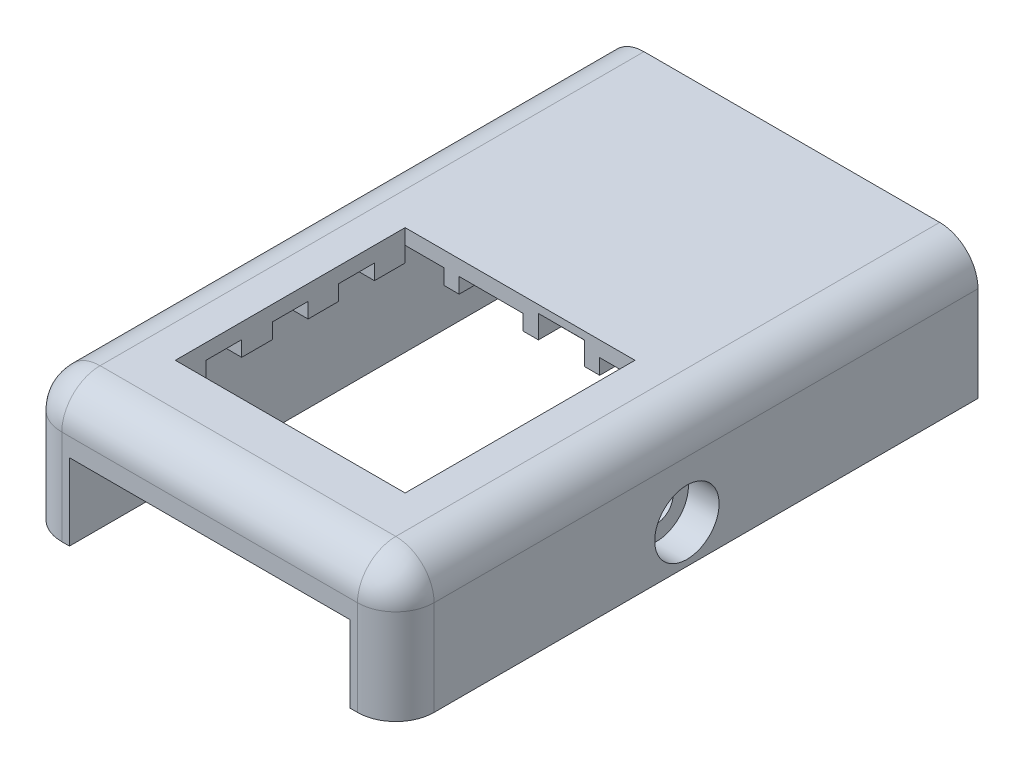
SolidWorks part; units mm, degrees
ref_plane "Front Plane" through (0, 0, 0) normal (0, 0, 1) x (1, 0, 0)
ref_plane "Top Plane" through (0, 0, 0) normal (0, 1, 0) x (1, 0, 0)
ref_plane "Right Plane" through (0, 0, 0) normal (1, 0, 0) x (0, 0, -1)
sketch "Sketch1" plane through (0, 0, 0) normal (0, 1, 0) x (1, 0, 0)
  line L1 (0, 0) -> (18, 0) construction
  line L2 (0, 0) -> (0, 31) construction
  line L3 (0, 31) -> (18, 31) construction
  line L4 (18, 0) -> (18, 31) construction
  line L5 (-3.15, 37.7) -> (21.15, 37.7)
  line L6 (-3.15, 37.7) -> (-3.15, -0.3)
  line L7 (-3.15, -0.3) -> (21.15, -0.3)
  line L8 (21.15, 37.7) -> (21.15, -0.3)
  line L9 (9, 0) -> (9, -0.3) construction
  dimension "D1" = 18
  dimension "D2" = 31
  dimension "D4" = 0.3
  dimension "D5" = 38
extrude "base" add sketch "Sketch1" along normal blind 2
sketch "Sketch2" plane through (0, 0, 0) normal (0, -1, 0) x (1, 0, 0)
  line L0 (9, 0) -> (9, 0.15) construction
  line L1 (-3.15, 0.3) -> (21.15, 0.3)
  line L2 (-3.15, 0.3) -> (-3.15, -37.7)
  line L3 (-3.15, -37.7) -> (21.15, -37.7)
  line L4 (21.15, 0.3) -> (21.15, -37.7)
  line L5 (-0.15, 0.15) -> (18.15, 0.15)
  line L6 (-0.15, 0.15) -> (-0.15, -31.15)
  line L7 (-0.15, -31.15) -> (18.15, -31.15)
  line L8 (18.15, 0.15) -> (18.15, -31.15)
  line L9 (18, -15.5) -> (18.15, -15.5) construction
  line L10 (-0.15, -15.5) -> (0, -15.5) construction
  line L11 (9, -31.15) -> (9, -31) construction
  line L13 (0, 0) -> (18, 0) construction
  line L14 (0, 0) -> (0, -31) construction
  line L15 (0, -31) -> (18, -31) construction
  line L16 (18, 0) -> (18, -31) construction
  dimension "D1" = 0.15
  dimension "D2" = 18
  dimension "D3" = 31
extrude "pcb_edge_walls" add sketch "Sketch2" along normal blind 1.7
sketch "Sketch3" plane through (0, 0, 0) normal (0, -1, 0) x (1, 0, 0)
  line L2 (0, 0) -> (18, 0) construction
  line L3 (0, 0) -> (0, -31) construction
  line L4 (0, -31) -> (18, -31) construction
  line L5 (18, 0) -> (18, -31) construction
  circle A0 centre (1.5, -29.46) radius 0.95
  circle A1 centre (16.5, -29.46) radius 0.95
  circle A2 centre (9, -3) radius 0.95
  point P9 (9, 0)
  dimension "D1" = 1.9
  dimension "D2" = 18
  dimension "D3" = 31
  dimension "D4" = 1.5
  dimension "D5" = 1.54
  dimension "D6" = 1.5
  dimension "D7" = 1.54
  dimension "D8" = 3
extrude "pcb_mount_dowels" add sketch "Sketch3" along normal blind 1.6
sketch "Sketch4" plane through (0, 2, 0) normal (0, 1, 0) x (1, 0, 0)
  line L0 (9, 19.96) -> (9, 12.46) construction
  line L1 (1.5, 4.96) -> (16.5, 4.96)
  line L2 (1.5, 4.96) -> (1.5, 19.96)
  line L3 (1.5, 19.96) -> (16.5, 19.96)
  line L4 (16.5, 4.96) -> (16.5, 19.96)
  line L5 (9, 12.46) -> (1.5, 12.46) construction
  line L6 (-3.15, -0.3) -> (21.15, -0.3) construction
  line L8 (0, 0) -> (18, 0) construction
  line L9 (0, 0) -> (0, 31) construction
  line L10 (0, 31) -> (18, 31) construction
  line L11 (18, 0) -> (18, 31) construction
  point P10 (9, -0.3)
  dimension "D1" = 12.46
  dimension "D2" = 15
  dimension "D3" = 18
  dimension "D4" = 31
extrude "silicone_pad_hole" cut sketch "Sketch4" against normal through all
sketch "Sketch6" plane through (0, 0, 0) normal (0, -1, 0) x (1, 0, 0)
  line L1 (3.8, -28) -> (14.2, -28)
  line L2 (3.8, -28) -> (3.8, -25.2)
  line L3 (3.8, -25.2) -> (14.2, -25.2)
  line L4 (14.2, -28) -> (14.2, -25.2)
  line L6 (0, 0) -> (18, 0) construction
  line L7 (0, 0) -> (0, -31) construction
  line L8 (0, -31) -> (18, -31) construction
  line L9 (18, 0) -> (18, -31) construction
  point P4 (9, -31)
  point P5 (9, -28)
  dimension "D1" = 3.8
  dimension "D2" = 18
  dimension "D3" = 31
  dimension "D4" = 3
  dimension "D5" = 2.8
  dimension "D6" = 10.4
extrude "wire_solderings_hole" cut sketch "Sketch6" against normal blind 1.5
sketch "Sketch7" plane through (0, 0, 0) normal (0, -1, 0) x (1, 0, 0)
  line L0 (11.7, -19.95) -> (11.7, -20.7) construction
  line L1 (13.2, -21.45) -> (10.2, -21.45)
  line L2 (13.2, -21.45) -> (13.2, -19.95)
  line L3 (13.2, -19.95) -> (10.2, -19.95)
  line L4 (10.2, -21.45) -> (10.2, -19.95)
  line L5 (11.7, -20.7) -> (13.2, -20.7) construction
  line L7 (0, 0) -> (18, 0) construction
  line L8 (0, 0) -> (0, -31) construction
  line L9 (0, -31) -> (18, -31) construction
  line L10 (18, 0) -> (18, -31) construction
  dimension "D1" = 18
  dimension "D2" = 31
  dimension "D3" = 6.3
  dimension "D4" = 10.3
  dimension "D5" = 3
  dimension "D6" = 1.5
extrude "Cut-Extrude4" cut sketch "Sketch7" against normal blind 1.5
sketch "Sketch5" plane through (0, 0, 0) normal (0, -1, 0) x (1, 0, 0)
  line L0 (-0.15, -19.96) -> (-0.15, -24.2)
  line L1 (-0.15, -24.2) -> (18.15, -24.2)
  line L3 (14.2, -22.45) -> (9.2, -22.45)
  line L5 (16.5, -19.96) -> (13.2, -19.96) construction
  line L13 (9.2, -22.45) -> (9.2, -19.96)
  line L14 (9.2, -19.96) -> (14.2, -19.96)
  line L15 (14.2, -19.96) -> (14.2, -22.45)
  line L22 (-0.15, -0.72) -> (18.15, -0.72)
  line L24 (18.15, -0.72) -> (18.15, -24.2)
  line L25 (14.2, -25.2) -> (3.8, -25.2) construction
  line L26 (10.2, -21.45) -> (13.2, -21.45) construction
  line L28 (13.2, -21.45) -> (13.2, -19.96) construction
  line L30 (10.2, -19.96) -> (10.2, -21.45) construction
  line L31 (4.025, -19.96) -> (4.025, -21.45)
  line L32 (4.025, -21.45) -> (2.525, -21.45)
  line L33 (2.525, -21.45) -> (2.525, -22.45)
  line L34 (2.525, -22.45) -> (6.525, -22.45)
  line L35 (6.525, -22.45) -> (6.525, -21.45)
  line L36 (6.525, -21.45) -> (5.025, -21.45)
  line L37 (5.025, -21.45) -> (5.025, -19.96)
  line L38 (5.025, -19.96) -> (4.025, -19.96)
  line L39 (-0.15, -19.96) -> (9.2, -19.96) construction
  line L40 (-0.15, 0.15) -> (-0.15, -31.15) construction
  line L42 (-0.15, 0.15) -> (-0.15, -31.15) construction
  line L44 (18.15, -31.15) -> (18.15, 0.15) construction
  line L45 (16.5, -19.96) -> (16.5, -24.2) construction
  line L46 (16.5, -4.96) -> (16.5, -0.72) construction
  line L47 (3.8584, -4.96) -> (3.8584, -3.47)
  line L48 (1.5, -4.96) -> (16.5, -4.96) construction
  line L49 (3.8584, -3.47) -> (2.3584, -3.47)
  line L50 (2.3584, -3.47) -> (2.3584, -2.47)
  line L51 (2.3584, -2.47) -> (6.3584, -2.47)
  line L52 (6.3584, -2.47) -> (6.3584, -3.47)
  line L53 (6.3584, -3.47) -> (4.8584, -3.47)
  line L54 (4.8584, -3.47) -> (4.8584, -4.96)
  line L55 (4.8584, -4.96) -> (3.8584, -4.96)
  line L56 (13.1416, -4.96) -> (13.1416, -3.47)
  line L57 (13.1416, -3.47) -> (11.6416, -3.47)
  line L58 (11.6416, -3.47) -> (11.6416, -2.47)
  line L59 (11.6416, -2.47) -> (15.6416, -2.47)
  line L60 (15.6416, -2.47) -> (15.6416, -3.47)
  line L61 (15.6416, -3.47) -> (14.1416, -3.47)
  line L62 (14.1416, -3.47) -> (14.1416, -4.96)
  line L63 (14.1416, -4.96) -> (13.1416, -4.96)
  line L64 (4.3584, -2.47) -> (4.3584, -0.72) construction
  line L65 (4.3584, -1.595) -> (13.6416, -1.595) construction
  line L66 (13.6416, -2.47) -> (13.6416, -0.72) construction
  line L67 (1.5, -19.96) -> (1.5, -4.96) construction
  line L68 (1.5, -4.96) -> (0.5, -4.96)
  line L69 (1.5, -4.96) -> (1.5, -6.96)
  line L70 (1.5, -6.96) -> (0.5, -6.96)
  line L71 (0.5, -4.96) -> (0.5, -6.96)
  line L72 (-0.15, -0.72) -> (-0.15, -19.96)
  line L85 (1.5, -9.2933) -> (1.5, -11.2933)
  line L86 (1.5, -9.2933) -> (0.5, -9.2933)
  line L87 (0.5, -9.2933) -> (0.5, -11.2933)
  line L88 (1.5, -11.2933) -> (0.5, -11.2933)
  line L89 (1.5, -13.6267) -> (1.5, -15.6267)
  line L90 (1.5, -13.6267) -> (0.5, -13.6267)
  line L91 (0.5, -13.6267) -> (0.5, -15.6267)
  line L92 (1.5, -15.6267) -> (0.5, -15.6267)
  line L93 (1.5, -17.96) -> (1.5, -19.96)
  line L94 (1.5, -17.96) -> (0.5, -17.96)
  line L95 (0.5, -17.96) -> (0.5, -19.96)
  line L96 (1.5, -19.96) -> (0.5, -19.96)
  line L97 (9, -4.96) -> (9, -19.96) construction
  line L98 (16.5, -17.96) -> (17.5, -17.96)
  line L99 (17.5, -17.96) -> (17.5, -19.96)
  line L100 (16.5, -19.96) -> (17.5, -19.96)
  line L101 (16.5, -17.96) -> (16.5, -19.96)
  line L102 (16.5, -13.6267) -> (17.5, -13.6267)
  line L103 (17.5, -13.6267) -> (17.5, -15.6267)
  line L104 (16.5, -15.6267) -> (17.5, -15.6267)
  line L105 (16.5, -13.6267) -> (16.5, -15.6267)
  line L106 (16.5, -9.2933) -> (17.5, -9.2933)
  line L107 (17.5, -9.2933) -> (17.5, -11.2933)
  line L108 (16.5, -11.2933) -> (17.5, -11.2933)
  line L109 (16.5, -9.2933) -> (16.5, -11.2933)
  line L110 (16.5, -6.96) -> (17.5, -6.96)
  line L111 (17.5, -4.96) -> (17.5, -6.96)
  line L112 (16.5, -4.96) -> (17.5, -4.96)
  line L113 (16.5, -4.96) -> (16.5, -6.96)
  circle A0 centre (9, -3) radius 0.95 construction
  circle A1 centre (9, -3) radius 0.95
  point P15 (4.525, -19.96)
  point P19 (4.525, -19.96)
  point P32 (4.525, -22.45)
  point P62 (4.3584, -2.47)
  point P63 (4.3584, -4.96)
  point P64 (13.6416, -2.47)
  point P65 (13.6416, -4.96)
  point P72 (9, -0.72)
  point P73 (9, -1.595)
  dimension "D1" = 1
  dimension "D2" = 1
  dimension "D3" = 1
  dimension "D4" = 1
  dimension "D5" = 4
  dimension "D6" = 4
  dimension "D7" = 1
  dimension "D8" = 1
  dimension "D9" = 2
extrude "silicone_channels" cut sketch "Sketch5" against normal blind 1
sketch "Sketch8" plane through (-0.15, 0, 0) normal (1, 0, 0) x (0, 0, -1)
  line L0 (24.2, 1) -> (24.2, 0) construction
  line L1 (0.72, 0) -> (24.2, 0)
  line L2 (0.72, 0) -> (0.72, 1)
  line L3 (0.72, 1) -> (24.2, 1)
  line L4 (24.2, 0) -> (24.2, 1)
  line L5 (0.72, 1) -> (24.2, 1) construction
extrude "Cut-Extrude5" cut sketch "Sketch8" against normal blind 1
sketch "Sketch9" plane through (18.15, 0, 0) normal (-1, 0, 0) x (0, 0, 1)
  line L0 (-24.2, 1) -> (-0.72, 1) construction
  line L1 (-0.72, 0) -> (-24.2, 0)
  line L2 (-0.72, 0) -> (-0.72, 1)
  line L3 (-0.72, 1) -> (-24.2, 1)
  line L4 (-24.2, 0) -> (-24.2, 1)
extrude "Cut-Extrude6" cut sketch "Sketch9" against normal blind 1
fillet "Fillet1" radius 0.7 2 edges at (19.15, 0, -12.46) (-1.15, 0, -12.46)
sketch "Sketch17" plane through (0, -1.7, 0) normal (0, -1, 0) x (1, 0, 0)
  line L0 (-3.15, -37.7) -> (21.15, -37.7) construction
  line L1 (-3.15, 0.3) -> (-0.15, 0.3)
  line L2 (-3.15, 0.3) -> (-3.15, -37.7)
  line L3 (-3.15, -37.7) -> (-0.15, -37.7)
  line L4 (-0.15, 0.3) -> (-0.15, -37.7)
  line L5 (18.15, -31.15) -> (18.15, -24.2) construction
  line L6 (21.15, 0.3) -> (18.15, 0.3)
  line L7 (21.15, 0.3) -> (21.15, -37.7)
  line L8 (21.15, -37.7) -> (18.15, -37.7)
  line L9 (18.15, 0.3) -> (18.15, -37.7)
  line L10 (-0.15, 0.15) -> (-0.15, -31.15) construction
extrude "Boss-Extrude4" add sketch "Sketch17" along normal blind 5
sketch "Sketch19" plane through (-3.15, 0, 0) normal (-1, 0, 0) x (0, 0, 1)
  line L0 (0.3, -1.7) -> (-37.7, -1.7) construction
  line L1 (0.3, 2) -> (0.3, -6.7) construction
  line L2 (-37.7, 2) -> (-37.7, -6.7) construction
  line L3 (0.3, -1.7) -> (0.3, -6.7) construction
  line L4 (-37.7, -1.7) -> (-37.7, -6.7) construction
  line L5 (-37.7, -4.2) -> (0.3, -4.2) construction
  line L6 (-37.7, 2) -> (0.3, 2) construction
  circle A0 centre (-4.7, -4.2) radius 1.1
  circle A1 centre (-32.7, -4.2) radius 1.1
  dimension "D1" = 2.2
  dimension "D2" = 5
  dimension "D3" = 5
extrude "Cut-Extrude9" cut sketch "Sketch19" against normal blind 5
sketch "Sketch20" plane through (-3.15, 0, 0) normal (-1, 0, 0) x (0, 0, 1)
  circle A0 centre (-4.7, -4.2) radius 2.1
  circle A1 centre (-32.7, -4.2) radius 2.1
  dimension "D1" = 4.2
extrude "Cut-Extrude10" cut sketch "Sketch20" against normal blind 2
sketch "Sketch21" plane through (21.15, 0, 0) normal (1, 0, 0) x (0, 0, -1)
  line L0 (-0.3, -1.7) -> (37.7, -1.7) construction
  line L1 (-0.3, 2) -> (-0.3, -6.7) construction
  line L2 (37.7, 2) -> (37.7, -6.7) construction
  line L3 (-0.3, -1.7) -> (-0.3, -6.7) construction
  line L4 (37.7, -1.7) -> (37.7, -6.7) construction
  line L5 (-0.3, -4.2) -> (37.7, -4.2) construction
  line L6 (-0.3, 2) -> (37.7, 2) construction
  circle A0 centre (4.7, -4.2) radius 1.1 construction
  circle A1 centre (4.7, -4.2) radius 1.1 construction
  circle A2 centre (18.7, -4.2) radius 1.1
  circle A3 centre (32.7, -4.2) radius 1.1 construction
  circle A4 centre (32.7, -4.2) radius 1.1 construction
  point P20 (18.7, 2)
extrude "Cut-Extrude11" cut sketch "Sketch21" against normal blind 5
sketch "Sketch22" plane through (21.15, 0, 0) normal (1, 0, 0) x (0, 0, -1)
  circle A0 centre (18.7, -4.2) radius 2.1
  dimension "D1" = 4.2
extrude "Cut-Extrude12" cut sketch "Sketch22" against normal blind 2
fillet "Fillet3" radius 2.5 5 edges at (21.15, 2, -18.7) (21.15, -2.35, 0.3) (-3.15, -2.35, 0.3) (9, 2, 0.3) (-3.15, 2, -18.7)
